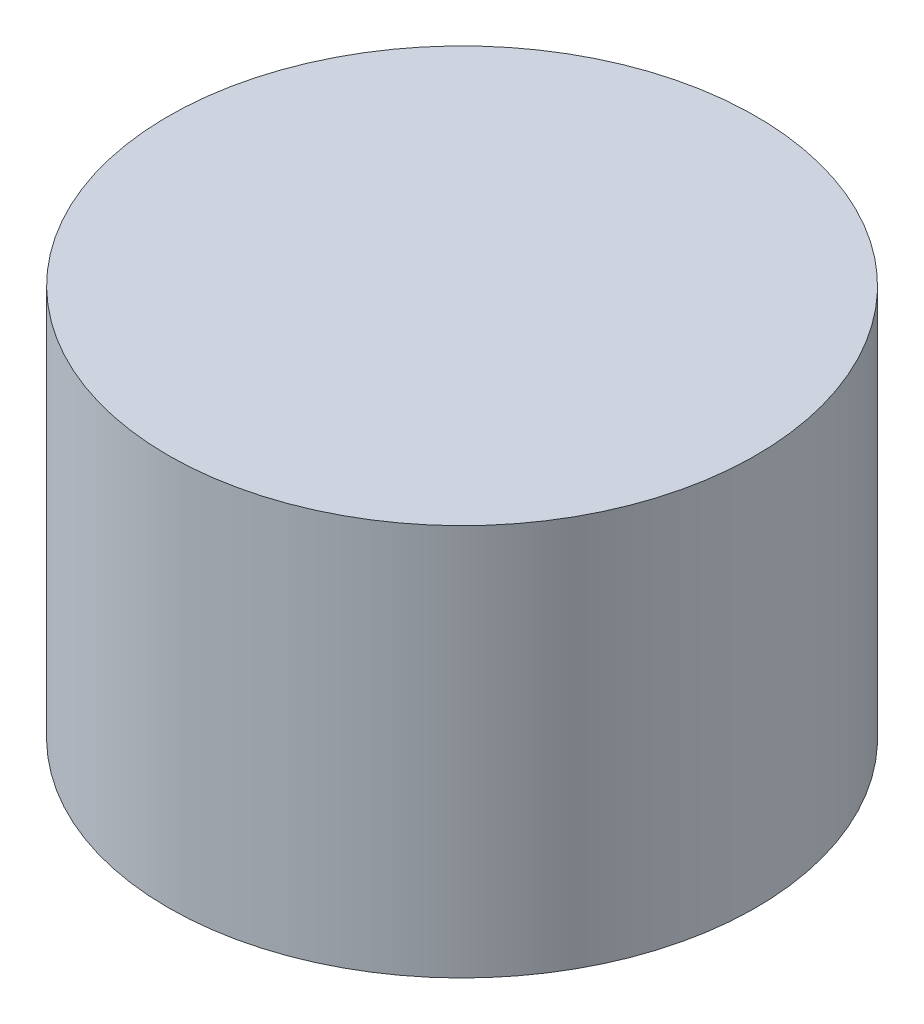
SolidWorks part; units mm, degrees
ref_plane "Front Plane" through (0, 0, 0) normal (0, 0, 1) x (1, 0, 0)
ref_plane "Top Plane" through (0, 0, 0) normal (0, 1, 0) x (1, 0, 0)
ref_plane "Right Plane" through (0, 0, 0) normal (1, 0, 0) x (0, 0, -1)
sketch "Sketch1" plane through (0, 0, 0) normal (0, 1, 0) x (1, 0, 0)
  circle A1 centre (0, 0) radius 3.81
extrude "Boss-Extrude1" add sketch "Sketch1" along normal blind 5.08
